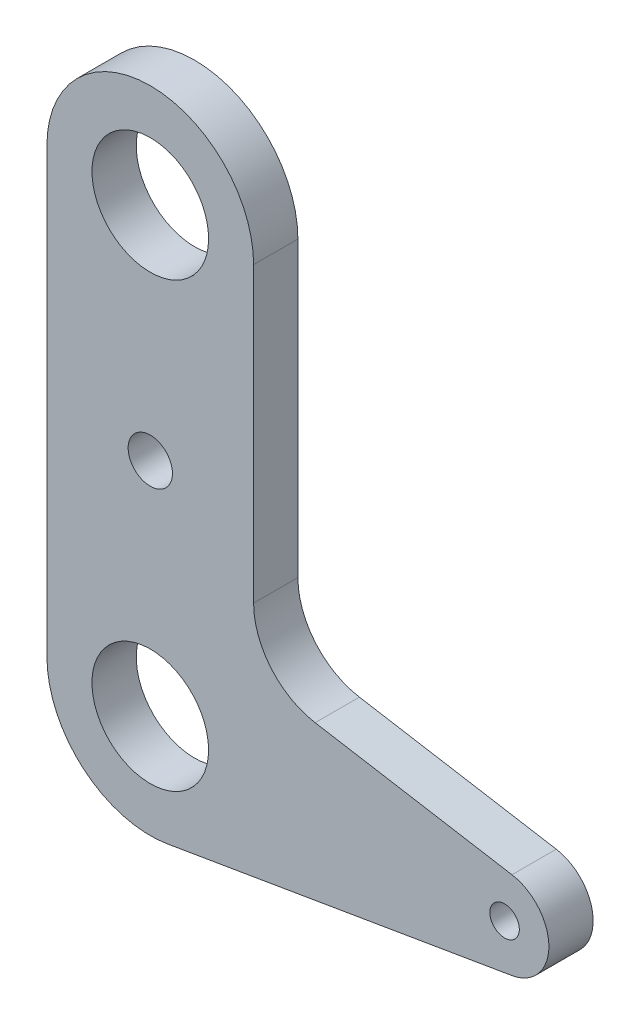
SolidWorks part; units mm, degrees
ref_plane "前视基准面" through (0, 0, 0) normal (0, 0, 1) x (1, 0, 0)
ref_plane "上视基准面" through (0, 0, 0) normal (0, 1, 0) x (1, 0, 0)
ref_plane "右视基准面" through (0, 0, 0) normal (1, 0, 0) x (0, 0, -1)
sketch "草图1" plane through (0, 0, 0) normal (0, 0, 1) x (1, 0, 0)
  line L0 (-7, 30) -> (-7, 0)
  line L1 (7, 30) -> (7, 0)
  line L2 (1.1667, 6.9021) -> (24.5, 2.958)
  line L3 (0, 0) -> (16.3963, 0)
  line L4 (1.1667, -6.9021) -> (24.5, -2.958)
  circle A0 centre (0, 0) radius 3.95
  circle A1 centre (0, 30) radius 3.95
  circle A3 centre (0, 30) radius 7
  circle A4 centre (0, 0) radius 7
  circle A6 centre (24, 0) radius 1
  circle A7 centre (24, 0) radius 3
  circle A8 centre (0, 15) radius 1.5
  dimension "D1" = 14
  dimension "D2" = 7.9
  dimension "D3" = 30
  dimension "D4" = 24
  dimension "D5" = 6
  dimension "D6" = 2
  dimension "D7" = 3
  dimension "D9" = 7.9
  dimension "D8" = 15
extrude "凸台-拉伸1" add sketch "草图1" along normal blind 3
fillet "圆角1" radius 5 1 edges at (7, 5.9161, 1.5)
